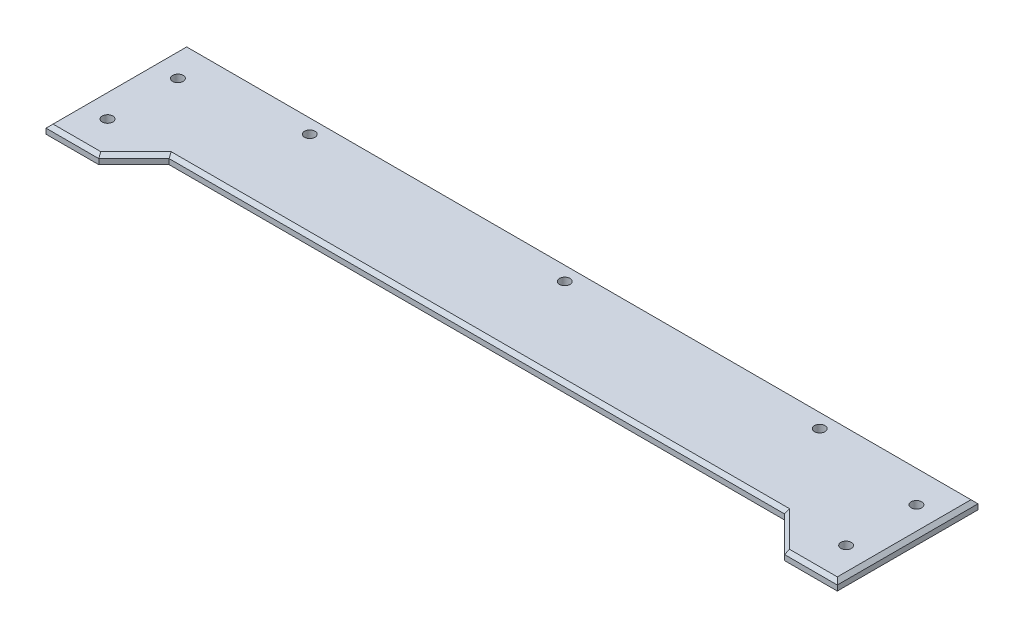
SolidWorks part; units mm, degrees
ref_plane "Alzado" through (0, 0, 0) normal (0, 0, 1) x (1, 0, 0)
ref_plane "Planta" through (0, 0, 0) normal (0, 1, 0) x (1, 0, 0)
ref_plane "Vista lateral" through (0, 0, 0) normal (1, 0, 0) x (0, 0, -1)
sketch "Croquis1" plane through (0, 0, 0) normal (0, 1, 0) x (1, 0, 0)
  line L0 (-149.6078, -39.6078) -> (-129.6078, -19.6078)
  line L1 (-179.6078, 40.3922) -> (270.3922, 40.3922)
  line L2 (-179.6078, 40.3922) -> (-179.6078, -39.6078)
  line L3 (-179.6078, -39.6078) -> (-149.6078, -39.6078)
  line L4 (270.3922, 40.3922) -> (270.3922, -39.6078)
  line L5 (-129.6078, -19.6078) -> (220.3922, -19.6078)
  line L6 (220.3922, -19.6078) -> (240.3922, -39.6078)
  line L7 (240.3922, -39.6078) -> (270.3922, -39.6078)
  circle A0 centre (-164.6078, 20.3922) radius 3
  circle A1 centre (-99.6078, 30.3922) radius 3
  circle A2 centre (190.3922, 30.3922) radius 3
  circle A3 centre (45.3922, 30.3922) radius 3
  circle A4 centre (-164.6078, -19.6078) radius 3
  circle A5 centre (255.3922, 20.3922) radius 3
  circle A6 centre (255.3922, -19.6078) radius 3
  dimension "D3" = 6
  dimension "D4" = 6
  dimension "D5" = 6
  dimension "D6" = 6
  dimension "D7" = 6
  dimension "D8" = 6
  dimension "D9" = 6
  dimension "D1" = 80
  dimension "D2" = 450
  dimension "D10" = 15
  dimension "D11" = 10
  dimension "D12" = 225
  dimension "D13" = 80
  dimension "D14" = 80
  dimension "D15" = 15
  dimension "D16" = 20
  dimension "D17" = 20
  dimension "D18" = 30
  dimension "D19" = 30
  dimension "D20" = 45
  dimension "D21" = 45
extrude "Saliente-Extruir1" add sketch "Croquis1" along normal blind 5
chamfer "Chaflán1" distance 2 angle 45 8 edges at (270.3922, 5, -0.3922) (45.3922, 5, -40.3922) (-179.6078, 5, -0.3922) (-164.6078, 5, 39.6078) (-139.6078, 5, 29.6078) (45.3922, 5, 19.6078) (230.3922, 5, 29.6078) (255.3922, 5, 39.6078)
